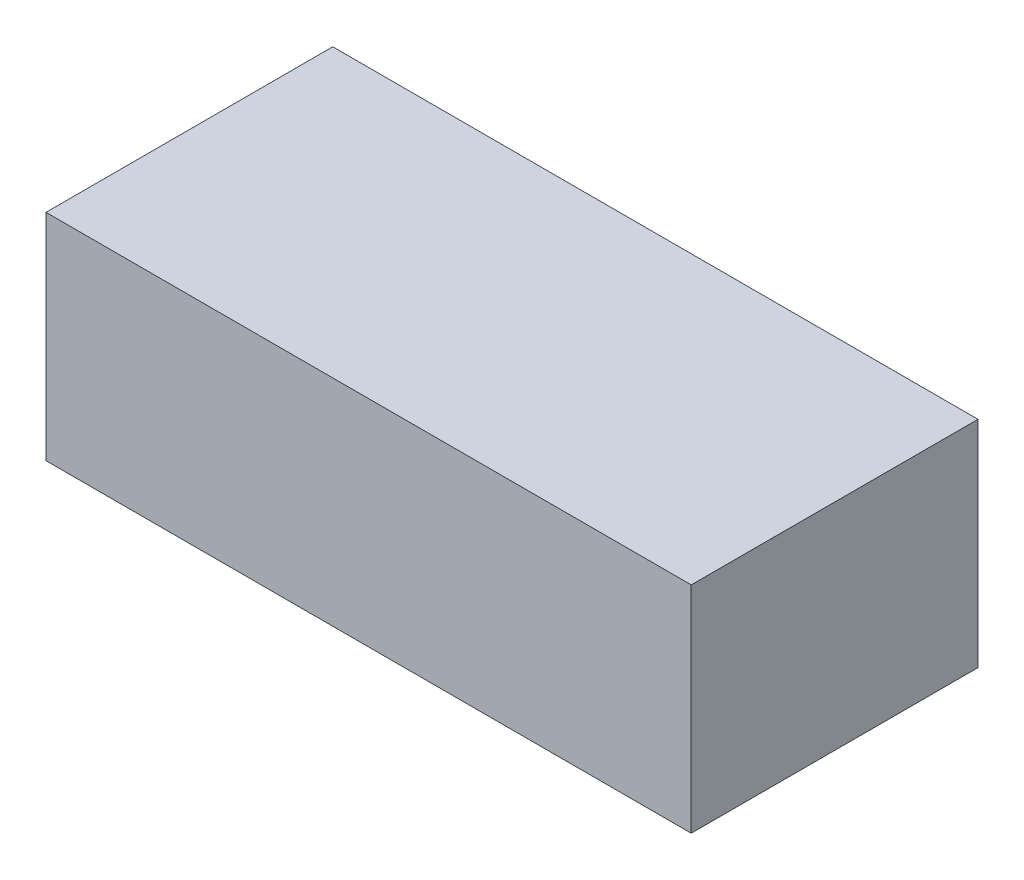
SolidWorks part; units mm, degrees
ref_plane "Front Plane" through (0, 0, 0) normal (0, 0, 1) x (1, 0, 0)
ref_plane "Top Plane" through (0, 0, 0) normal (0, 1, 0) x (1, 0, 0)
ref_plane "Right Plane" through (0, 0, 0) normal (1, 0, 0) x (0, 0, -1)
sketch "Sketch1" plane through (0, 0, 0) normal (0, 1, 0) x (1, 0, 0)
  line L1 (-776.6129, 268.5484) -> (1023.3871, 268.5484)
  line L2 (-776.6129, 268.5484) -> (-776.6129, -531.4516)
  line L3 (-776.6129, -531.4516) -> (1023.3871, -531.4516)
  line L4 (1023.3871, 268.5484) -> (1023.3871, -531.4516)
  dimension "D1" = 1800
  dimension "D2" = 800
extrude "Boss-Extrude1" add sketch "Sketch1" along normal blind 600
